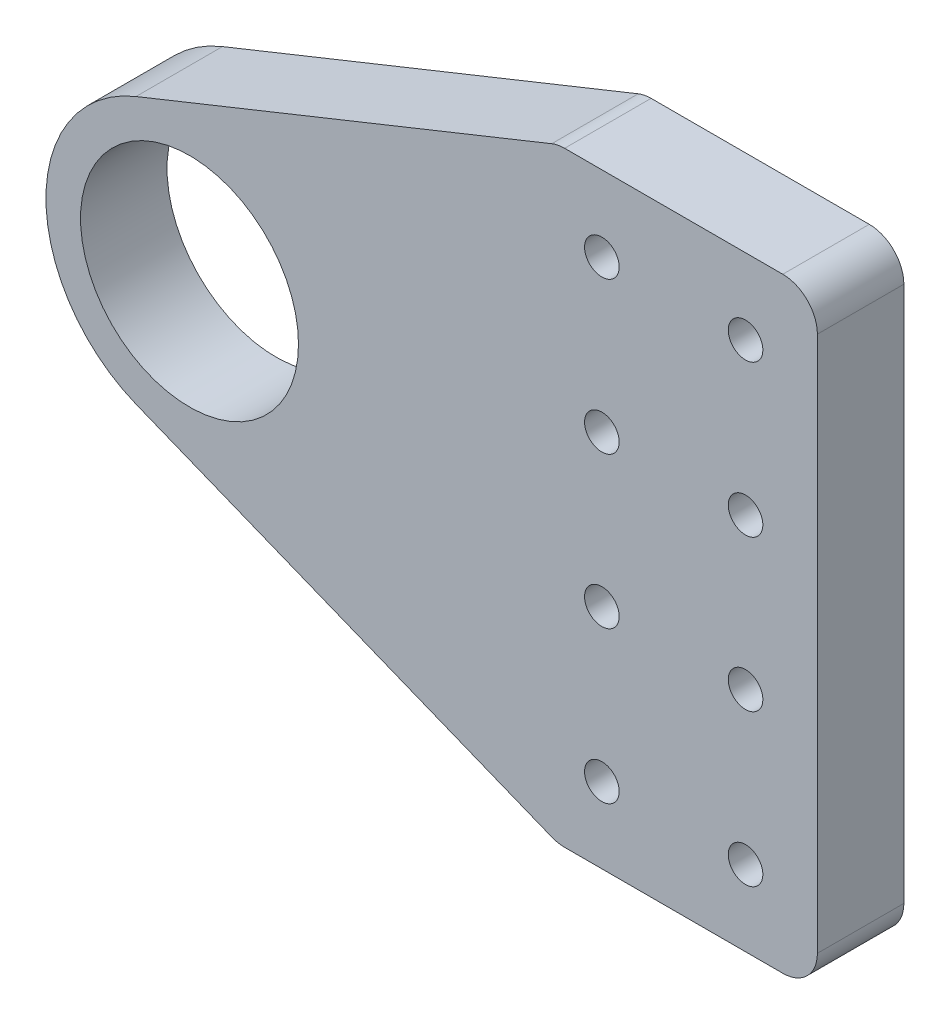
SolidWorks part; units mm, degrees
ref_plane "Front Plane" through (0, 0, 0) normal (0, 0, 1) x (1, 0, 0)
ref_plane "Top Plane" through (0, 0, 0) normal (0, 1, 0) x (1, 0, 0)
ref_plane "Right Plane" through (0, 0, 0) normal (1, 0, 0) x (0, 0, -1)
sketch "Sketch1" plane through (0, 0, 0) normal (0, 0, 1) x (1, 0, 0)
  line L0 (877.2821, -292.1) -> (909.32, -292.1)
  line L1 (914.4, -287.02) -> (914.4, -208.28)
  line L2 (914.4, -225.3961) -> (893.301, -203.2) construction
  line L3 (893.301, -203.2) -> (893.301, -50203.2) construction
  line L4 (876.3, -292.1) -> (876.3, 0) construction
  line L5 (875.3887, -291.7339) -> (814.3403, -267.2129)
  line L6 (838.2, -247.1633) -> (838.2, -50247.1633) construction
  line L7 (821.055, -247.65) -> (50821.055, -247.65) construction
  line L8 (877.2821, -203.2) -> (909.32, -203.2)
  line L9 (875.3887, -203.5661) -> (814.3403, -228.0871)
  line L10 (914.4, -225.425) -> (-49085.6, -225.425) construction
  line L11 (914.4, -269.875) -> (-49085.6, -269.875) construction
  line L12 (893.301, -203.2) -> (893.301, -225.425) construction
  line L13 (893.301, -225.425) -> (914.4, -203.2) construction
  circle A0 centre (822.198, -247.65) radius 16.002
  arc A1 (814.3403, -228.0871) -> (814.3403, -267.2129) centre (822.198, -247.65) ccw
  circle A2 centre (903.8505, -214.298) radius 2.54
  circle A3 centre (882.7516, -214.298) radius 2.54
  circle A4 centre (882.7516, -236.552) radius 2.54
  circle A5 centre (903.8505, -236.552) radius 2.54
  circle A6 centre (882.7516, -258.748) radius 2.54
  circle A7 centre (882.7516, -281.002) radius 2.54
  circle A8 centre (903.8505, -258.748) radius 2.54
  circle A9 centre (903.8505, -281.002) radius 2.54
  arc A10 (877.2821, -203.2) -> (875.3887, -203.5661) centre (877.2821, -208.28) ccw
  arc A11 (877.2821, -292.1) -> (875.3887, -291.7339) centre (877.2821, -287.02) cw
  arc A12 (909.32, -292.1) -> (914.4, -287.02) centre (909.32, -287.02) ccw
  arc A13 (909.32, -203.2) -> (914.4, -208.28) centre (909.32, -208.28) cw
  circle A14 centre (822.198, -247.65) radius 5.08 construction
  point P13 (893.301, -203.2)
  point P31 (903.8505, -214.298)
  point P46 (876.3, -203.2)
  point P49 (876.3, -292.1)
  point P52 (914.4, -292.1)
  dimension "D1" = 32.004
  dimension "D2" = 5.08
  dimension "D5" = 5.08
  dimension "D6" = 5.08
  dimension "D3" = 38.1
  dimension "D4" = 44.45
  dimension "D8" = 22.225
extrude "Boss-Extrude1" add sketch "Sketch1" along normal blind 12.7
